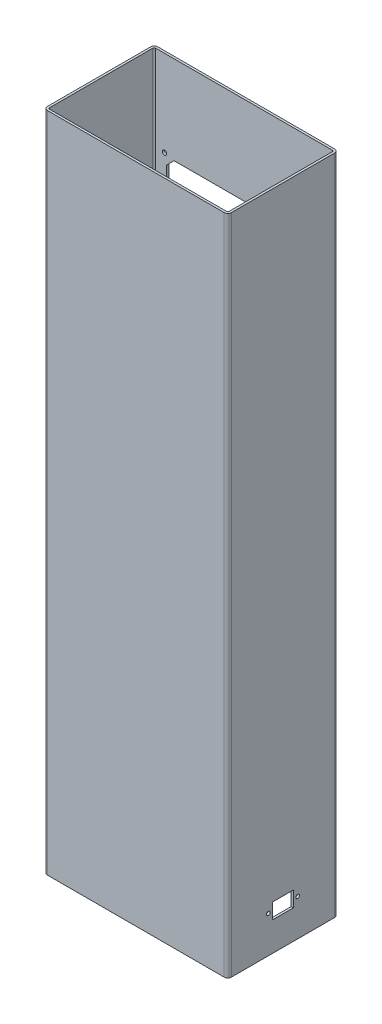
SolidWorks part; units mm, degrees
material "PW80:Mi:0:41:Ar:0:-1:C1:1:2:3:Re:15:"
ref_plane "Plan1" through (0, 0, 0) normal (0, 0, 1) x (1, 0, 0)
ref_plane "Plan2" through (0, 0, 0) normal (0, 1, 0) x (1, 0, 0)
ref_plane "Plan3" through (0, 0, 0) normal (1, 0, 0) x (0, 0, -1)
sketch "Esquisse1" plane through (0, 0, 0) normal (0, 1, 0) x (1, 0, 0)
  line L1 (0, 0) -> (250, 0)
  line L2 (0, 0) -> (0, 150)
  line L3 (0, 150) -> (250, 150)
  line L4 (250, 0) -> (250, 150)
extrude "Base-Extrusion" add sketch "Esquisse1" along normal blind 900
fillet "Congé2" radius 5
shell "Coque1" thickness 3
sketch "Esquisse3" plane through (0, 0, -150) normal (0, 0, -1) x (-1, 0, 0)
  line L0 (-230, 770) -> (-220, 780)
  line L1 (-220, 780) -> (-30, 780)
  line L2 (-230, 770) -> (-230, 460)
  line L3 (-220, 450) -> (-30, 450)
  line L4 (-20, 770) -> (-20, 460)
  line L5 (-30, 780) -> (-20, 770)
  line L6 (-20, 460) -> (-30, 450)
  line L7 (-220, 450) -> (-230, 460)
extrude "Enlèv. mat.-Extru.2" cut sketch "Esquisse3" against normal blind 10
sketch "Esquisse4" plane through (0, 0, -150) normal (0, 0, -1) x (-1, 0, 0)
  circle A0 centre (-17, 783) radius 3
  circle A1 centre (-17, 447) radius 3
  circle A2 centre (-233, 783) radius 3
  circle A3 centre (-233, 447) radius 3
extrude "Enlèv. mat.-Extru.3" cut sketch "Esquisse4" against normal blind 10
sketch "Esquisse6" plane through (250, 0, 0) normal (1, 0, 0) x (0, 0, -1)
  line L1 (61, 60.5) -> (89, 60.5)
  line L2 (61, 60.5) -> (61, 39.5)
  line L3 (61, 39.5) -> (89, 39.5)
  line L4 (89, 60.5) -> (89, 39.5)
  circle A0 centre (95, 50) radius 2.5
  circle A1 centre (55, 50) radius 2.5
extrude "Enlèv. mat.-Extru.4" cut sketch "Esquisse6" against normal blind 8
